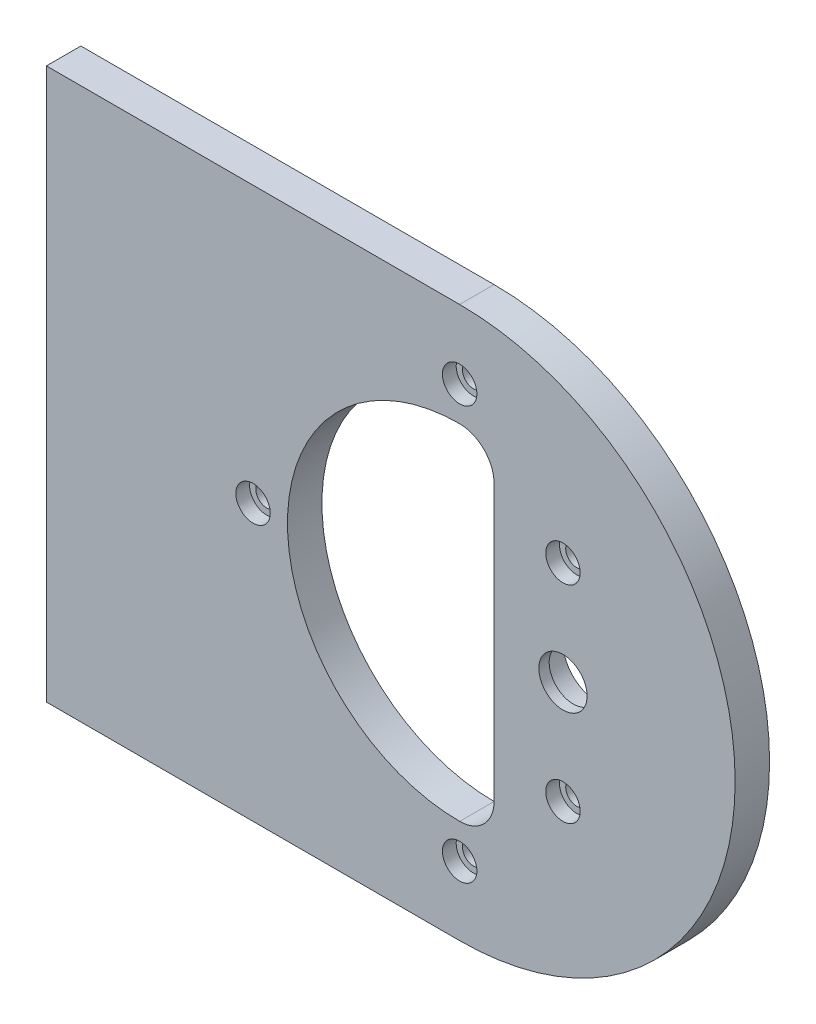
SolidWorks part; units mm, degrees
ref_plane "前视基准面" through (0, 0, 0) normal (0, 0, 1) x (1, 0, 0)
ref_plane "上视基准面" through (0, 0, 0) normal (0, 1, 0) x (1, 0, 0)
ref_plane "右视基准面" through (0, 0, 0) normal (1, 0, 0) x (0, 0, -1)
sketch "草图1" plane through (0, 0, 0) normal (0, 0, 1) x (1, 0, 0)
  line L3 (66.4575, 70) -> (6.4575, 70)
  line L4 (6.4575, 70) -> (6.4575, -10)
  line L5 (6.4575, -10) -> (66.4575, -10)
  arc A1 (66.4575, -10) -> (66.4575, 70) centre (66.4575, 30) ccw
extrude "凸台-拉伸1" add sketch "草图1" along normal blind 5
sketch "草图3" plane through (0, 0, 0) normal (0, 0, 1) x (1, 0, 0)
  line L1 (71.4575, 35) -> (71.4575, 50)
  line L2 (71.4575, 35) -> (71.4575, 10)
  arc A0 (66.4575, 5) -> (71.4575, 10) centre (66.4575, 10) ccw
  arc A1 (66.4575, 55) -> (66.4575, 5) centre (66.4575, 30) ccw
  arc A2 (71.4575, 50) -> (66.4575, 55) centre (66.4575, 50) ccw
  dimension "D1" = 5
extrude "切除-拉伸2" cut sketch "草图3" along normal blind 10
sketch "草图4" plane through (0, 0, 0) normal (0, 0, 1) x (1, 0, 0)
  circle A1 centre (81.4575, 30) radius 5
extrude "切除-拉伸3" cut sketch "草图4" along normal blind 3.5 contours A1
ref_plane "基准面1" through (0, 0, 5) normal (0, 0, 1) x (1, 0, 0)
sketch "草图8" plane through (0, 0, 0) normal (0, 0, 1) x (1, 0, 0)
  circle A1 centre (66.4575, 67.5) radius 1
  circle A2 centre (92.974, 56.5165) radius 1
  circle A3 centre (103.9575, 30) radius 1
  circle A4 centre (92.974, 3.4835) radius 1
  circle A5 centre (66.4575, -7.5) radius 1
  circle A6 centre (39.941, 3.4835) radius 1
  circle A7 centre (28.9575, 30) radius 1
  circle A8 centre (39.941, 56.5165) radius 1
  dimension "D1" = 8
sketch "草图9" plane through (0, 0, 0) normal (0, 0, 1) x (1, 0, 0)
  circle A0 centre (81.4575, 45) radius 1.6
  circle A1 centre (66.4575, 60) radius 1.6
  circle A2 centre (81.4575, 15) radius 1.6
  circle A3 centre (66.4575, 0) radius 1.6
  circle A4 centre (36.4575, 30) radius 1.6
  circle A5 centre (96.4575, 30) radius 1.6 [skipped]
  dimension "D1" = 4
sketch "草图10" plane through (0, 0, 5) normal (0, 0, 1) x (1, 0, 0)
  circle A0 centre (66.4575, 60) radius 2.5
  circle A1 centre (81.4575, 45) radius 2.5
  circle A2 centre (66.4575, 0) radius 2.5
  circle A3 centre (36.4575, 30) radius 2.5
  circle A4 centre (81.4575, 15) radius 2.5
extrude "切除-拉伸7" cut sketch "草图8" along normal blind 1
extrude "切除-拉伸8" cut sketch "草图10" against normal blind 2
extrude "切除-拉伸9" cut sketch "草图9" along normal blind 3
sketch "草图11" plane through (0, 0, 5) normal (0, 0, 1) x (1, 0, 0)
  circle A0 centre (81.4575, 30) radius 3.5
extrude "切除-拉伸10" cut sketch "草图11" against normal blind 10
